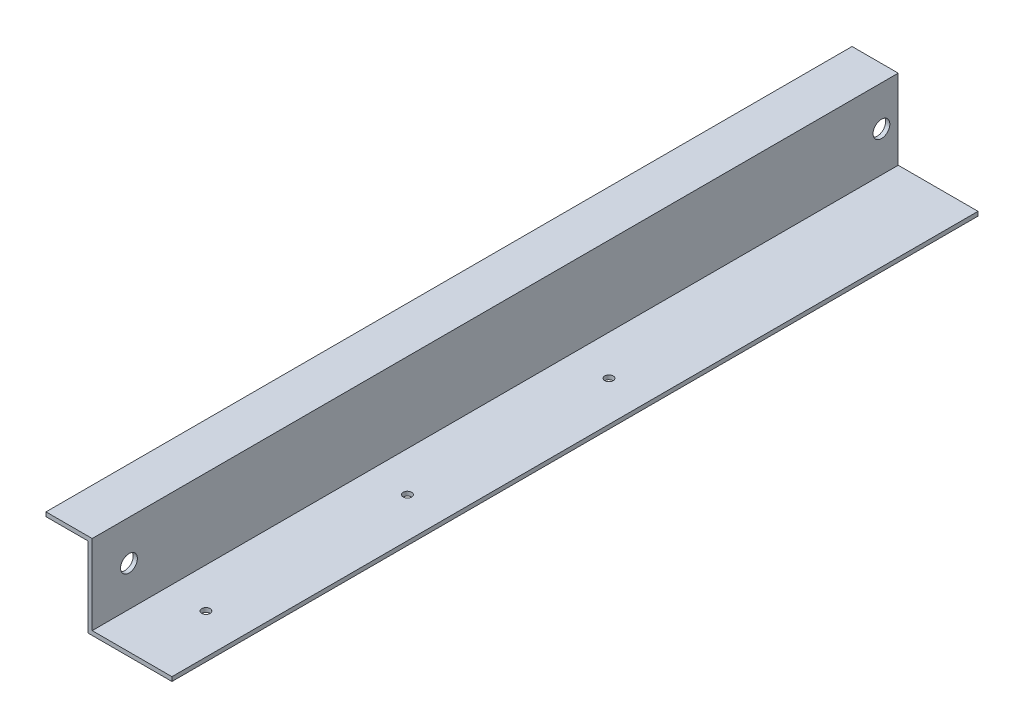
SolidWorks part; units mm, degrees
ref_plane "Front Plane" through (0, 0, 0) normal (0, 0, 1) x (1, 0, 0)
ref_plane "Top Plane" through (0, 0, 0) normal (0, 1, 0) x (1, 0, 0)
ref_plane "Right Plane" through (0, 0, 0) normal (1, 0, 0) x (0, 0, -1)
sketch "Sketch1" plane through (0, 0, 0) normal (0, 0, 1) x (1, 0, 0)
  line L0 (0, -15.0813) -> (0, 15.0813) construction
  line L1 (0, 15.0813) -> (-30.9563, 15.0813) construction
  line L2 (0, -15.0813) -> (30.9563, -15.0812) construction
  line L3 (0.7937, -14.2875) -> (30.9563, -14.2875) construction
  line L4 (0.7937, -14.2875) -> (0.7937, 15.875) construction
  line L5 (0.7937, 15.875) -> (-30.9563, 15.875) construction
  line L6 (-0.7937, -15.875) -> (30.9563, -15.875) construction
  line L7 (-0.7937, -15.875) -> (-0.7937, 14.2875) construction
  line L8 (-0.7937, 14.2875) -> (-30.9563, 14.2875) construction
  line L9 (-30.9563, 15.875) -> (-30.9563, 14.2875) construction
  line L10 (30.9563, -14.2875) -> (30.9563, -15.875) construction
  point P4 (0, 0)
  dimension "Leg Width" = 31.75
  dimension "Outside Height" = 31.75
  dimension "Wall Thickness" = 1.5875
sketch "Sketch2" plane through (0, 0, 0) normal (1, 0, 0) x (0, 0, -1)
  line L0 (152.4, 0) -> (-152.4, 0) construction
  line L1 (0, 0) -> (0, 15.875) construction
  line L2 (-152.4, 0) -> (-152.4, 15.875) construction
  line L3 (152.4, 0) -> (152.4, 15.875) construction
  point P0 (-114.3, 0)
  point P3 (114.3, 0)
  point P4 (0, 0)
  dimension "D1" = 228.6
  dimension "Length" = 304.8
sketch "Sketch3" plane through (0, 0, 0) normal (0, 0, 1) x (1, 0, 0)
  line L0 (30.9563, -14.2875) -> (30.9563, -15.875) construction
  line L3 (-0.7937, -15.875) -> (-0.7937, 14.2875) construction
  line L4 (0.7937, -14.2875) -> (0.7937, 15.875) construction
  line L8 (30.9563, -14.2875) -> (30.9563, -15.875)
  line L9 (0.7937, -14.2875) -> (30.9563, -14.2875)
  line L10 (-0.7937, -15.875) -> (30.9563, -15.875)
  line L11 (-0.7937, -15.875) -> (-0.7937, 14.2875)
  line L12 (0.7937, -14.2875) -> (0.7937, 15.875)
  line L13 (0.7937, 15.875) -> (-16.6687, 15.875)
  line L14 (-16.6687, 15.875) -> (-16.6687, 14.2875)
  line L15 (-0.7937, 14.2875) -> (-16.6687, 14.2875)
extrude "Boss-Extrude1" add sketch "Sketch3" along normal up to vertex (152.4 mm away) and the other way up to vertex (152.4 mm away) up to point (0, 0, 152.4) other way up to point (0, 0, -152.4)
sketch "Sketch4" plane through (0, -14.2875, 0) normal (0, 1, 0) x (1, 0, 0)
  line L1 (0.7937, -152.4) -> (0.7937, 152.4) construction
  line L2 (15.875, -152.4) -> (15.875, -133.35) construction
  line L3 (30.9563, -152.4) -> (0.7937, -152.4) construction
  line L4 (15.875, -133.35) -> (15.875, -124.46) construction
  line L5 (15.875, -124.46) -> (15.875, -48.26) construction
  line L6 (15.875, -48.26) -> (15.875, 27.94) construction
  circle A0 centre (15.875, 27.94) radius 1.5875
  circle A1 centre (15.875, -48.26) radius 1.5875
  circle A2 centre (15.875, -124.46) radius 1.5875
  dimension "D1" = 76.2
  dimension "D2" = 76.2
  dimension "D3" = 19.05
  dimension "D4" = 15.0812
extrude "Cut-Extrude1" cut sketch "Sketch4" against normal blind 1.5875
sketch "Sketch5" plane through (0.7937, 0, 0) normal (1, 0, 0) x (0, 0, -1)
  line L0 (-152.4, 0.7937) -> (-138.4808, 0.7937) construction
  line L1 (-152.4, -14.2875) -> (-152.4, 15.875) construction
  line L2 (152.4, 0.7937) -> (146.05, 0.7937) construction
  line L3 (152.4, -14.2875) -> (152.4, 15.875) construction
  line L6 (-152.4, 15.875) -> (152.4, 15.875) construction
  circle A0 centre (-138.4808, 0.7937) radius 3.175
  circle A1 centre (146.05, 0.7937) radius 3.175
  dimension "D1" = 13.9192
  dimension "D3" = 6.35
  dimension "D2" = 6.35
  dimension "D4" = 15.0813
extrude "Cut-Extrude2" cut sketch "Sketch5" against normal blind 1.5875
equation "\"D1@Sketch2\"=\"Length@Sketch2\"*0.75"
